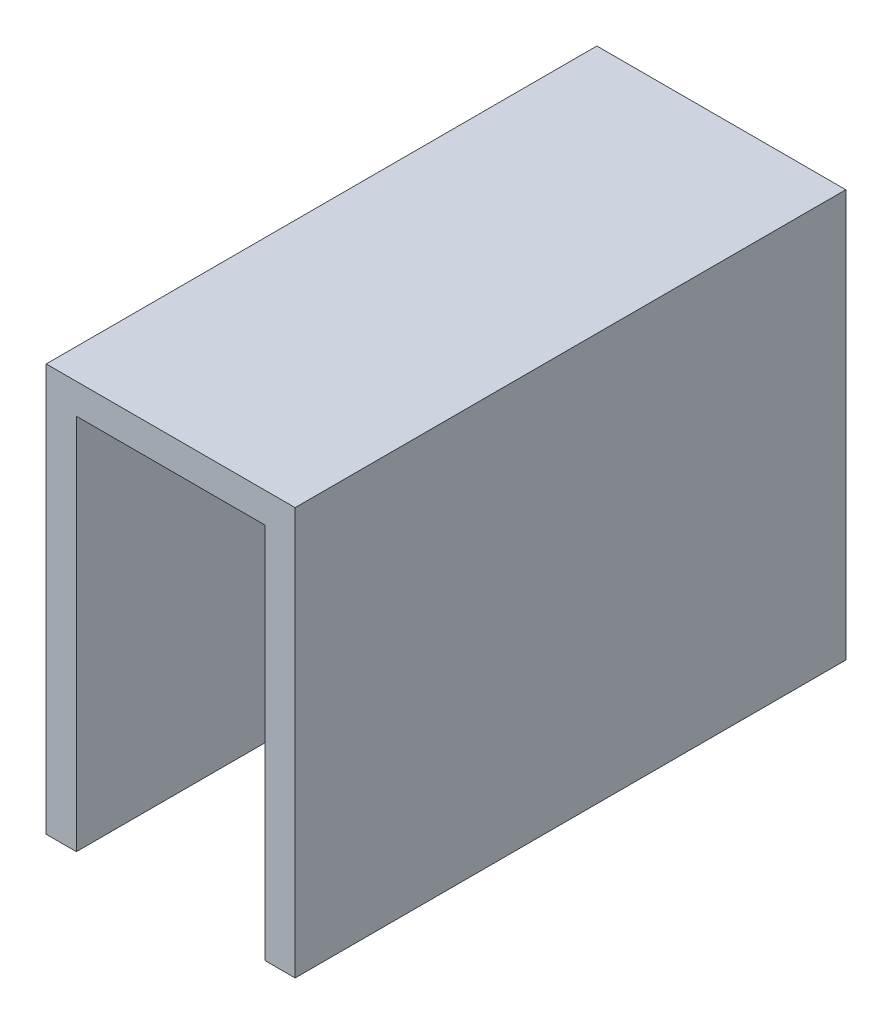
SolidWorks part; units mm, degrees
ref_plane "Alzado" through (0, 0, 0) normal (0, 0, 1) x (1, 0, 0)
ref_plane "Planta" through (0, 0, 0) normal (0, 1, 0) x (1, 0, 0)
ref_plane "Vista lateral" through (0, 0, 0) normal (1, 0, 0) x (0, 0, -1)
sketch "Croquis1" plane through (0, 0, 0) normal (0, 0, 1) x (1, 0, 0)
  line L0 (-16.5, 29) -> (-16.5, -29)
  line L1 (-12.5, 25) -> (12.5, 25)
  line L2 (-12.5, 25) -> (-12.5, -25)
  line L3 (-12.5, -25) -> (12.5, -25)
  line L4 (12.5, 25) -> (12.5, -25)
  line L5 (-16.5, -29) -> (16.5, -29)
  line L6 (16.5, 29) -> (16.5, -29)
  line L7 (-16.5, 29) -> (16.5, 29)
  point P4 (0, -25)
  point P6 (0, 25)
  point P7 (-12.5, 0)
  point P8 (12.5, 0)
  dimension "D1" = 25
  dimension "D2" = 50
  dimension "D3" = 4
extrude "Saliente-Extruir1" add sketch "Croquis1" along normal blind 70
sketch "Croquis2" plane through (0, 0, 0) normal (0, 0, -1) x (-1, 0, 0)
  line L4 (16.5, 29) -> (-16.5, 29)
  line L5 (-16.5, 29) -> (-16.5, -29)
  line L6 (-16.5, -29) -> (16.5, -29)
  line L7 (16.5, -29) -> (16.5, 29)
  line L8 (16.5, 29) -> (-16.5, 29)
  line L9 (-16.5, 29) -> (-16.5, -29)
  line L10 (-16.5, -29) -> (16.5, -29)
  line L11 (16.5, -29) -> (16.5, 29)
  dimension "D1" = 0
extrude "Saliente-Extruir2" add sketch "Croquis2" along normal blind 3
sketch "Croquis3" plane through (0, 0, 70) normal (0, 0, 1) x (1, 0, 0)
  line L0 (-16.5, 29) -> (-16.5, -29) construction
  line L1 (-16.5, -25) -> (16.5, -25)
  line L2 (-16.5, -25) -> (-16.5, -29)
  line L3 (-16.5, -29) -> (16.5, -29)
  line L4 (16.5, -25) -> (16.5, -29)
  line L5 (-12.5, -25) -> (12.5, -25) construction
extrude "Cortar-Extruir1" cut sketch "Croquis3" against normal through all
